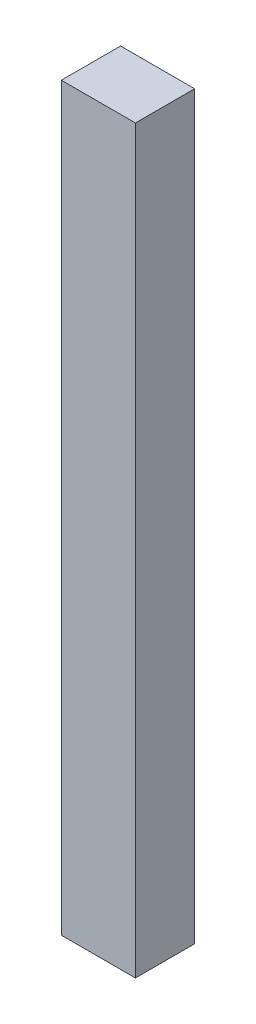
SolidWorks part; units mm, degrees
ref_plane "Front Plane" through (0, 0, 0) normal (0, 0, 1) x (1, 0, 0)
ref_plane "Top Plane" through (0, 0, 0) normal (0, 1, 0) x (1, 0, 0)
ref_plane "Right Plane" through (0, 0, 0) normal (1, 0, 0) x (0, 0, -1)
sketch "Sketch1" plane through (0, 0, 0) normal (0, 1, 0) x (1, 0, 0)
  line L0 (0, 0) -> (0, 10.16)
  line L1 (0, 10.16) -> (12.7, 10.16)
  line L2 (12.7, 10.16) -> (12.7, 0)
  line L3 (12.7, 0) -> (0, 0)
  dimension "D1" = 10.16
  dimension "D2" = 12.7
extrude "Boss-Extrude1" add sketch "Sketch1" along normal blind 127
